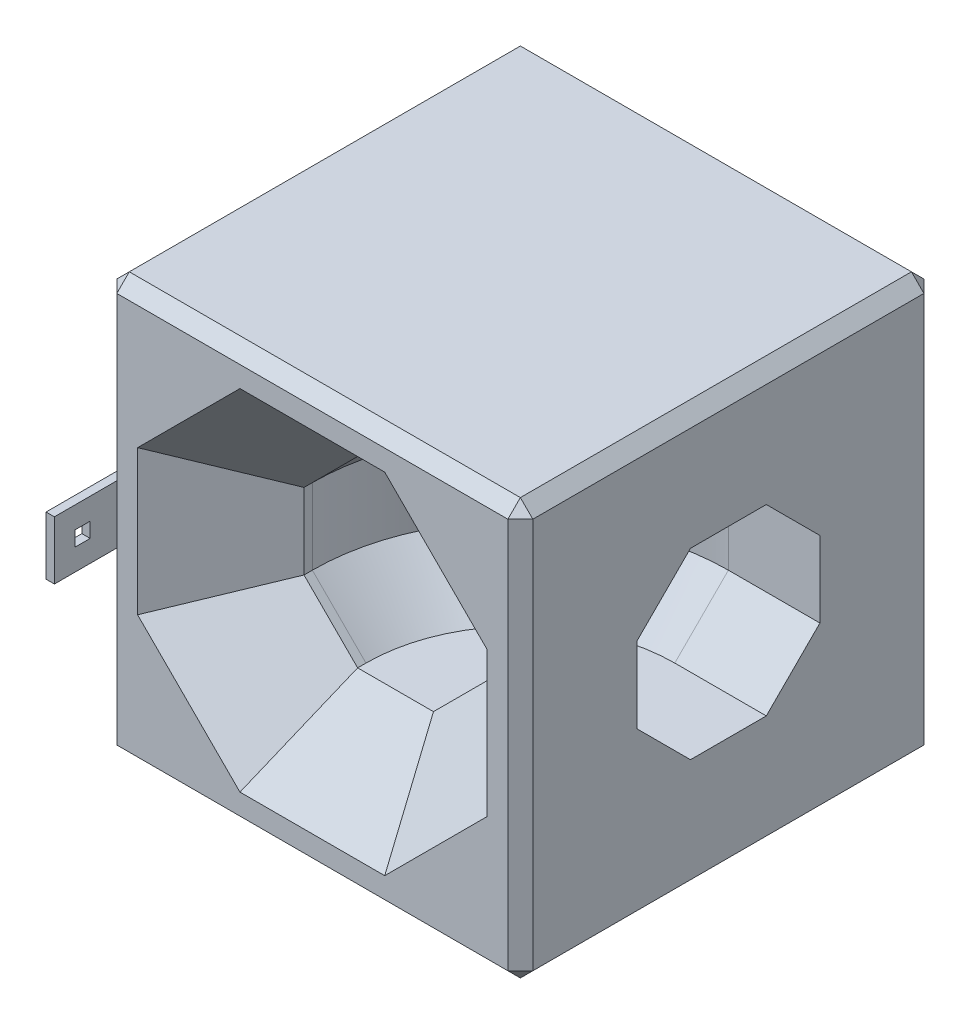
SolidWorks part; units mm, degrees
ref_plane "Front" through (0, 0, 0) normal (0, 0, 1) x (1, 0, 0)
ref_plane "Top" through (0, 0, 0) normal (0, 1, 0) x (1, 0, 0)
ref_plane "Right" through (0, 0, 0) normal (1, 0, 0) x (0, 0, -1)
sketch "Sketch1" plane through (0, 0, 0) normal (0, 0, 1) x (1, 0, 0)
  line L1 (0, 0) -> (50, 0)
  line L2 (0, 0) -> (0, 50)
  line L3 (0, 50) -> (50, 50)
  line L4 (50, 0) -> (50, 50)
  dimension "D1" = 50
extrude "Boss-Extrude1" add sketch "Sketch1" along normal blind 50
ref_plane "Plane1" through (0, 25, 0) normal (0, -1, 0) x (-1, 0, 0)
sketch "Sketch8" plane through (50, 0, 0) normal (1, 0, 0) x (0, 0, -1)
  line L0 (-25, 0) -> (-25, 25) construction
  line L1 (-14, 14) -> (-36, 14) construction
  line L2 (-14, 14) -> (-14, 36) construction
  line L3 (-14, 36) -> (-36, 36) construction
  line L4 (-36, 14) -> (-36, 36) construction
  line L5 (-14, 14) -> (-36, 36) construction
  line L6 (-14, 36) -> (-36, 14) construction
  line L7 (-25, 25) -> (0, 25) construction
  line L8 (-50, 0) -> (0, 0) construction
  line L9 (0, 0) -> (0, 50) construction
  line L11 (-14, 29.5563) -> (-20.4437, 36)
  line L12 (-20.4437, 36) -> (-29.5563, 36)
  line L13 (-29.5563, 36) -> (-36, 29.5563)
  line L14 (-36, 29.5563) -> (-36, 20.4437)
  line L15 (-36, 20.4437) -> (-29.5563, 14)
  line L16 (-29.5563, 14) -> (-20.4437, 14)
  line L17 (-20.4437, 14) -> (-14, 20.4437)
  line L18 (-14, 20.4437) -> (-14, 29.5563)
  circle A0 centre (-25, 25) radius 11 construction
  point P0 (-25, 25)
  dimension "D1" = 22
sketch "Sketch9" plane through (0, 25, 0) normal (0, -1, 0) x (-1, 0, 0)
  line L0 (-50, -25) -> (-39, -25)
  line L1 (-25, -39) -> (-25, -50)
  line L2 (-50, -50) -> (0, -50) construction
  arc A0 (-39, -25) -> (-25, -39) centre (-39, -39) cw
  dimension "D2" = 11
sweep "Cut-Sweep5" cut profiles "Sketch8" path "Sketch9"
chamfer "Chamfer1" distance 10 angle 45 8 edges at (36, 25, 50) (32.7782, 32.7782, 50) (25, 36, 50) (17.2218, 32.7782, 50) (14, 25, 50) (17.2218, 17.2218, 50) (25, 14, 50) (32.7782, 17.2218, 50)
chamfer "Chamfer2" distance 1.5 angle 45 12 edges at (25, 50, 0) (0, 50, 25) (0, 25, 0) (0, 0, 25) (25, 0, 0) (50, 25, 0) (50, 0, 25) (25, 0, 50) (50, 50, 25) (50, 25, 50) (0, 25, 50) (25, 50, 50)
sketch "Sketch10" plane through (0, 0, 50) normal (0, 0, 1) x (1, 0, 0)
  line L0 (0, 1.5) -> (0, 48.5) construction
  line L1 (0, 28.5) -> (1, 28.5)
  line L2 (0, 28.5) -> (0, 21.5)
  line L3 (0, 21.5) -> (1, 21.5)
  line L4 (1, 28.5) -> (1, 21.5)
  point P6 (0, 25)
  dimension "D1" = 1
  dimension "D2" = 7
extrude "Boss-Extrude2" add sketch "Sketch10" along normal blind 7 and the other way blind 10
sketch "Sketch11" plane through (1, 0, 0) normal (1, 0, 0) x (0, 0, -1)
  line L0 (-54.5, 25) -> (-57, 25) construction
  line L1 (-54.5, 24.1) -> (-52.7, 24.1)
  line L2 (-54.5, 24.1) -> (-54.5, 25.9)
  line L3 (-54.5, 25.9) -> (-52.7, 25.9)
  line L4 (-52.7, 24.1) -> (-52.7, 25.9)
  line L5 (-57, 21.5) -> (-57, 28.5) construction
  dimension "D1" = 1.8
  dimension "D2" = 2.5
extrude "Cut-Extrude1" cut sketch "Sketch11" against normal blind 7
